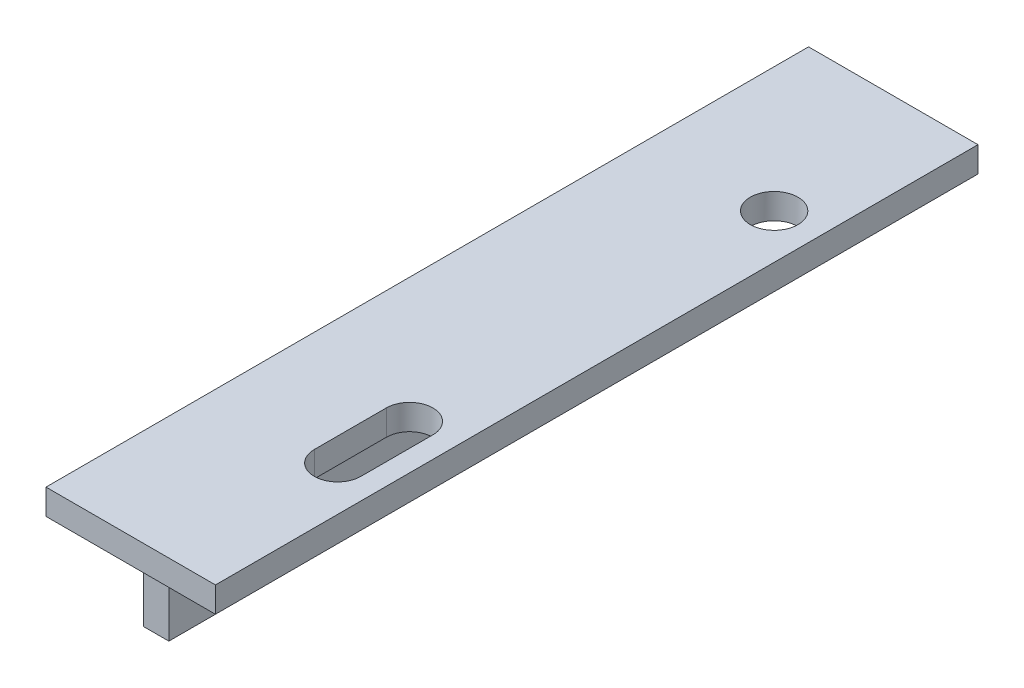
SolidWorks part; units mm, degrees
ref_plane "Front Plane" through (0, 0, 0) normal (0, 0, 1) x (1, 0, 0)
ref_plane "Top Plane" through (0, 0, 0) normal (0, 1, 0) x (1, 0, 0)
ref_plane "Right Plane" through (0, 0, 0) normal (1, 0, 0) x (0, 0, -1)
sketch "Sketch1" plane through (0, 0, 0) normal (0, 0, 1) x (1, 0, 0)
  line L0 (0, 0) -> (40, 0)
  line L1 (0, 0) -> (0, -40)
  line L2 (6, -6) -> (6, -40)
  line L3 (6, -6) -> (40, -6)
  line L4 (40, 0) -> (40, -6)
  line L5 (6, -40) -> (0, -40)
  dimension "D1" = 40
  dimension "D2" = 40
  dimension "D3" = 6
extrude "Boss-Extrude2" add sketch "Sketch1" against normal blind 180
sketch "Sketch3" plane through (6, 0, 0) normal (1, 0, 0) x (0, 0, -1)
  line L0 (180, -40) -> (0, -40) construction
  line L1 (0, -6) -> (23, -6)
  line L2 (0, -6) -> (0, -40)
  line L3 (0, -40) -> (23, -40)
  line L4 (23, -6) -> (23, -40)
  line L6 (180, -6) -> (157, -6)
  line L7 (180, -6) -> (180, -40)
  line L8 (180, -40) -> (157, -40)
  line L9 (157, -6) -> (157, -40)
  dimension "D1" = 23
  dimension "D2" = 23
extrude "Cut-Extrude2" cut sketch "Sketch3" against normal blind 10
sketch "Sketch4" plane through (0, 0, 0) normal (0, 1, 0) x (1, 0, 0)
  line L0 (40, 180) -> (0, 180) construction
  line L1 (0, 180) -> (0, 0) construction
  line L2 (29.48, 56.35) -> (29.48, 39.35) construction
  line L3 (34.98, 56.35) -> (34.98, 39.35)
  line L4 (23.98, 56.35) -> (23.98, 39.35)
  line L5 (40, 0) -> (0, 0) construction
  circle A0 centre (29.48, 142.4) radius 5.625
  arc A1 (34.98, 56.35) -> (23.98, 56.35) centre (29.48, 56.35) ccw
  arc A2 (23.98, 39.35) -> (34.98, 39.35) centre (29.48, 39.35) ccw
  point P8 (29.48, 47.85)
  point P13 (29.48, 33.85)
  dimension "D1" = 11.25
  dimension "D2" = 37.6
  dimension "D3" = 29.48
  dimension "D4" = 11
  dimension "D5" = 17
  dimension "D6" = 33.85
extrude "Cut-Extrude3" cut sketch "Sketch4" against normal blind 10
